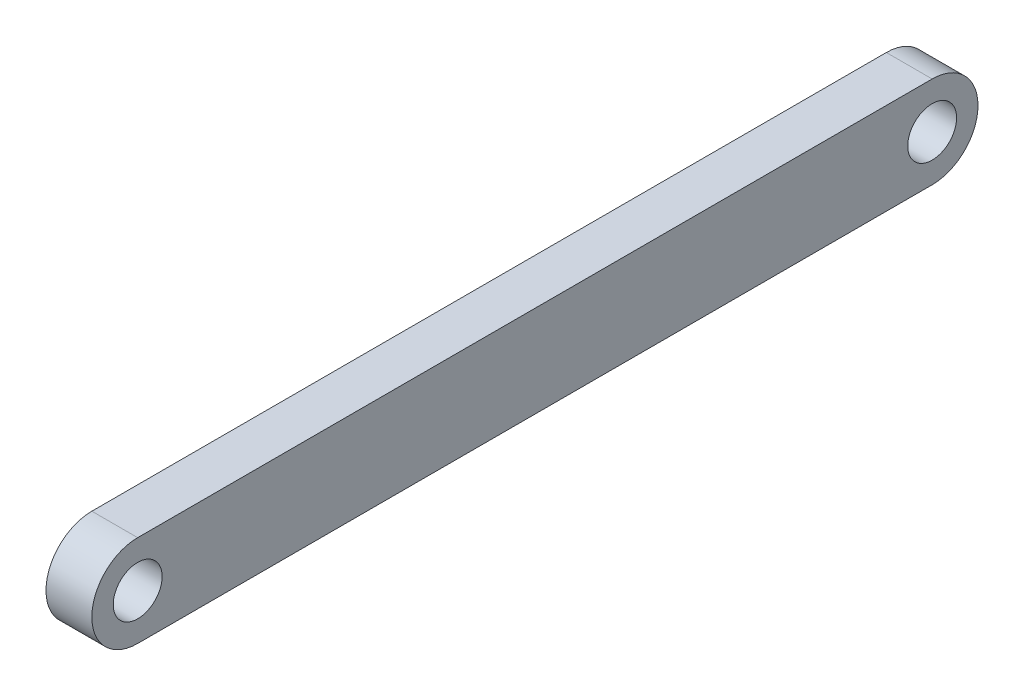
SolidWorks part; units mm, degrees
ref_plane "Front Plane" through (0, 0, 0) normal (1, 0, 0) x (0, 1, 0)
ref_plane "Top Plane" through (0, 0, 0) normal (0, 0, 1) x (0, 1, 0)
ref_plane "Right Plane" through (0, 0, 0) normal (0, 1, 0) x (-1, 0, 0)
sketch "Sketch1" plane through (0, 0, 0) normal (1, 0, 0) x (0, 1, 0)
  line L0 (-3, 52) -> (-3, 0)
  line L1 (3, 52) -> (3, 0)
  arc A0 (-3, 0) -> (3, 0) centre (0, 0) ccw
  arc A1 (3, 52) -> (-3, 52) centre (0, 52) ccw
  circle A2 centre (0, 52) radius 1.6
  circle A3 centre (0, 0) radius 1.6
  dimension "D1" = 6
  dimension "D2" = 6
  dimension "D4" = 3.2
  dimension "D5" = 3.2
  dimension "D3" = 52
extrude "Boss-Extrude1" add sketch "Sketch1" along normal blind 3
